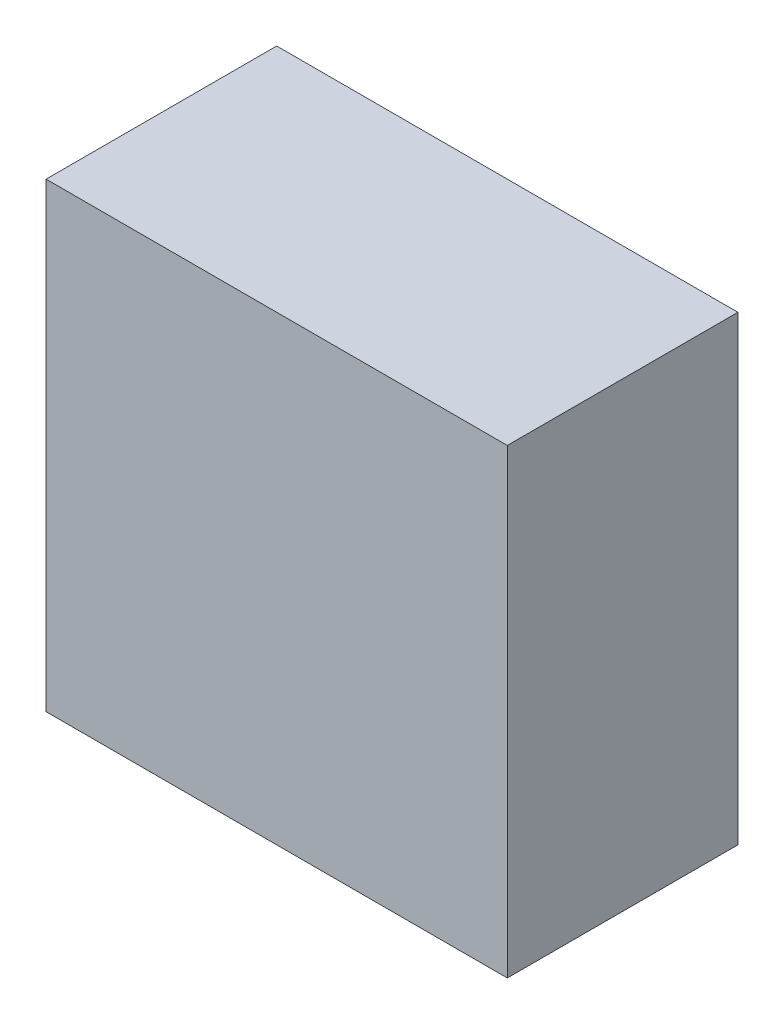
SolidWorks part; units mm, degrees
ref_plane "Front Plane" through (0, 0, 0) normal (0, 0, 1) x (1, 0, 0)
ref_plane "Top Plane" through (0, 0, 0) normal (0, 1, 0) x (1, 0, 0)
ref_plane "Right Plane" through (0, 0, 0) normal (1, 0, 0) x (0, 0, -1)
sketch "Sketch1" plane through (0, 0, 0) normal (0, 0, 1) x (1, 0, 0)
  line L0 (-1, 1) -> (1, 1)
  line L1 (1, 1) -> (1, -1)
  line L2 (1, -1) -> (-1, -1)
  line L3 (-1, -1) -> (-1, 1)
extrude "Component_Outline" add sketch "Sketch1" along normal blind 1 separate body
sketch3d "3DSketch1"
  line L0 (0, 0, 0) -> (1, 0, 0)
  line L1 (0, 0, 0) -> (0, 1, 0)
  line L2 (0, 0, 0) -> (0, 0, 1)
  point P0 (0, 0, 0)
